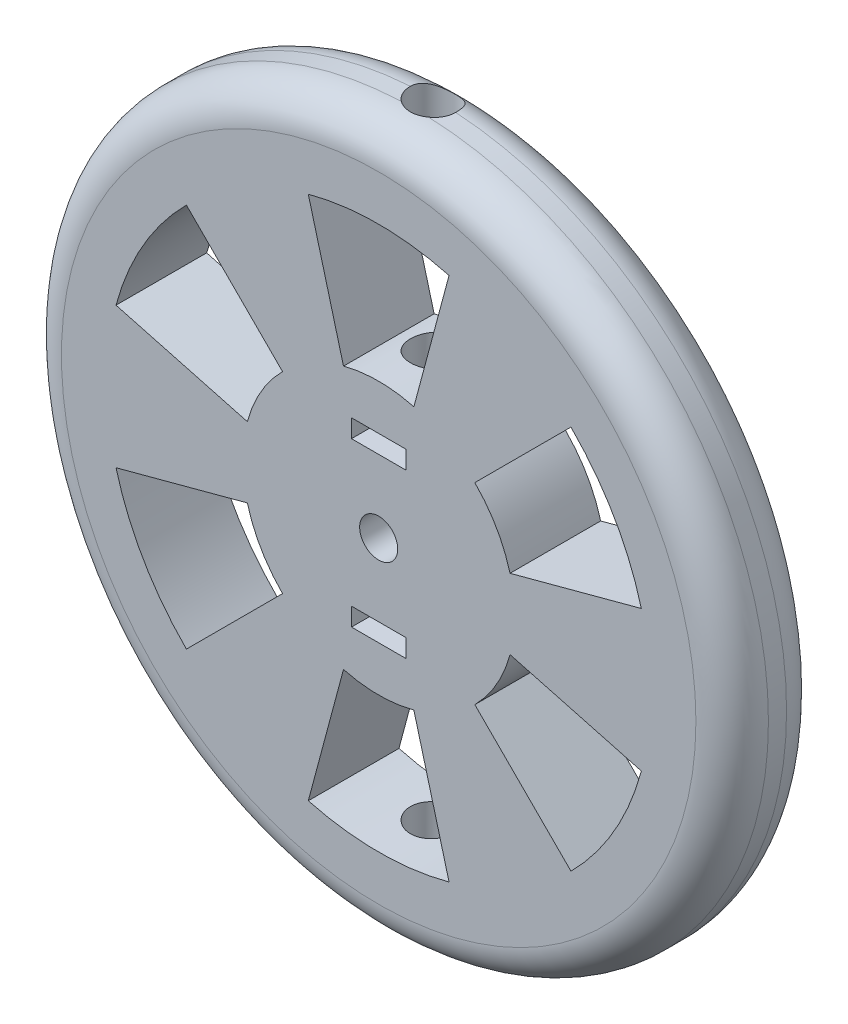
SolidWorks part; units mm, degrees
material "ABS"
ref_plane "Alzado" through (0, 0, 0) normal (0, 0, 1) x (1, 0, 0)
ref_plane "Planta" through (0, 0, 0) normal (0, 1, 0) x (1, 0, 0)
ref_plane "Vista lateral" through (0, 0, 0) normal (1, 0, 0) x (0, 0, -1)
sketch "Sketch1" plane through (0, 0, 0) normal (0, 0, 1) x (1, 0, 0)
  circle A0 centre (0, 0) radius 39
  dimension "D1" = 78
extrude "Boss-Extrude1" add sketch "Sketch1" along normal blind 10
sketch "Sketch2" plane through (0, 0, 10) normal (0, 0, 1) x (1, 0, 0)
  circle A1 centre (0, 0) radius 2.1
  dimension "D1" = 4.2
extrude "Cut-Extrude1" cut sketch "Sketch2" against normal through all
fillet "Fillet1" radius 4 2 edges at (39, 0, 10) (39, 0, 0)
sketch "Sketch3" plane through (0, 0, 10) normal (0, 0, 1) x (1, 0, 0)
  line L0 (0, 0) -> (7.7646, 28.9778) construction
  line L1 (0, 0) -> (-7.7646, 28.9778) construction
  line L2 (7.7646, 28.9778) -> (3.8823, 14.4889)
  line L3 (-7.7646, 28.9778) -> (-3.8823, 14.4889)
  line L4 (0, 0) -> (0, 35) construction
  line L5 (21.2132, 21.2132) -> (10.6066, 10.6066)
  line L6 (28.9778, 7.7646) -> (14.4889, 3.8823)
  line L7 (28.9778, -7.7646) -> (14.4889, -3.8823)
  line L8 (21.2132, -21.2132) -> (10.6066, -10.6066)
  line L9 (7.7646, -28.9778) -> (3.8823, -14.4889)
  line L10 (-7.7646, -28.9778) -> (-3.8823, -14.4889)
  line L11 (-21.2132, -21.2132) -> (-10.6066, -10.6066)
  line L12 (-28.9778, -7.7646) -> (-14.4889, -3.8823)
  line L13 (-28.9778, 7.7646) -> (-14.4889, 3.8823)
  line L14 (-21.2132, 21.2132) -> (-10.6066, 10.6066)
  arc A0 (3.8823, 14.4889) -> (-3.8823, 14.4889) centre (0, 0) ccw
  arc A1 (7.7646, 28.9778) -> (-7.7646, 28.9778) centre (0, 0) ccw
  circle A2 centre (0, 0) radius 35 construction
  arc A3 (14.4889, 3.8823) -> (10.6066, 10.6066) centre (0, 0) ccw
  arc A4 (28.9778, 7.7646) -> (21.2132, 21.2132) centre (0, 0) ccw
  arc A5 (10.6066, -10.6066) -> (14.4889, -3.8823) centre (0, 0) ccw
  arc A6 (21.2132, -21.2132) -> (28.9778, -7.7646) centre (0, 0) ccw
  arc A7 (-3.8823, -14.4889) -> (3.8823, -14.4889) centre (0, 0) ccw
  arc A8 (-7.7646, -28.9778) -> (7.7646, -28.9778) centre (0, 0) ccw
  arc A9 (-14.4889, -3.8823) -> (-10.6066, -10.6066) centre (0, 0) ccw
  arc A10 (-28.9778, -7.7646) -> (-21.2132, -21.2132) centre (0, 0) ccw
  arc A11 (-10.6066, 10.6066) -> (-14.4889, 3.8823) centre (0, 0) ccw
  arc A12 (-21.2132, 21.2132) -> (-28.9778, 7.7646) centre (0, 0) ccw
  point P6 (0, 30)
  point P7 (0, 15)
  dimension "D1" = 30
  dimension "D2" = 15
  dimension "D3" = 15
extrude "Cut-Extrude2" cut sketch "Sketch3" against normal through all
sketch "Sketch4" plane through (0, 0, 10) normal (0, 0, 1) x (1, 0, 0)
  line L0 (0, 0) -> (0, 35) construction
  line L1 (-39, 0) -> (39, 0) construction
  line L2 (-3, 10) -> (3, 10)
  line L3 (-3, 10) -> (-3, 8)
  line L4 (-3, 8) -> (3, 8)
  line L5 (3, 10) -> (3, 8)
  line L6 (-3, 10) -> (3, 8) construction
  line L7 (-3, 8) -> (3, 10) construction
  line L8 (-3, -8) -> (3, -8)
  line L9 (3, -10) -> (3, -8)
  line L10 (-3, -10) -> (3, -10)
  line L11 (-3, -10) -> (-3, -8)
  circle A0 centre (0, 0) radius 35 construction
  circle A1 centre (0, 0) radius 39 construction
  point P6 (0, 9)
  dimension "D1" = 6
  dimension "D2" = 2
  dimension "D3" = 9
extrude "Cut-Extrude3" cut sketch "Sketch4" against normal through all
sketch "Sketch5" plane through (0, 8, 0) normal (0, 1, 0) x (1, 0, 0)
  line L0 (0, 0) -> (0, -10) construction
  line L2 (-35, -10) -> (35, -10) construction
  line L3 (7.7646, 0) -> (-7.7646, 0) construction
  circle A0 centre (0, -4) radius 2.5
  dimension "D1" = 5
  dimension "D2" = 4
extrude "Cut-Extrude4" cut sketch "Sketch5" against normal through all and the other way through all
